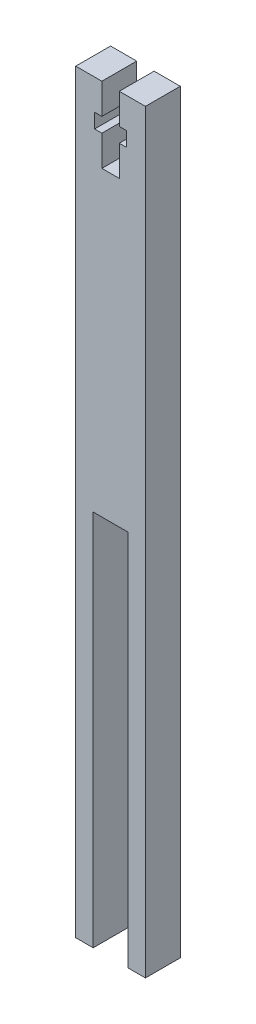
SolidWorks part; units mm, degrees
ref_plane "Спереди" through (0, 0, 0) normal (0, 0, 1) x (1, 0, 0)
ref_plane "Сверху" through (0, 0, 0) normal (0, 1, 0) x (1, 0, 0)
ref_plane "Справа" through (0, 0, 0) normal (1, 0, 0) x (0, 0, -1)
other "Configuration Table"
sketch "Эскиз1" plane through (0, 0, 0) normal (0, 0, 1) x (1, 0, 0)
  line L0 (0, 0) -> (0, 130) construction
  line L1 (0, 65) -> (-21.3565, 65) construction
  line L2 (-1.5, 130) -> (-1.5, 124.75)
  line L3 (-1.5, 124.75) -> (-2.75, 124.75)
  line L4 (-2.75, 124.75) -> (-2.75, 122.25)
  line L5 (-2.75, 122.25) -> (-1.5, 122.25)
  line L6 (-1.5, 122.25) -> (-1.5, 117)
  line L7 (-1.5, 117) -> (1.5, 117)
  line L8 (1.5, 122.25) -> (1.5, 117)
  line L9 (2.75, 122.25) -> (1.5, 122.25)
  line L10 (2.75, 124.75) -> (2.75, 122.25)
  line L11 (1.5, 124.75) -> (2.75, 124.75)
  line L12 (1.5, 130) -> (1.5, 124.75)
  line L25 (-1.5, 130) -> (-6, 130)
  line L26 (-6, 130) -> (-6, 0)
  line L28 (6, 130) -> (6, 0)
  line L29 (1.5, 130) -> (6, 130)
  line L30 (-6, 0) -> (-3, 0)
  line L31 (-3, 0) -> (-3, 65)
  line L32 (-3, 65) -> (3, 65)
  line L33 (3, 0) -> (3, 65)
  line L34 (6, 0) -> (3, 0)
  point P13 (0, 117)
  point P18 (2.75, 123.5)
  point P23 (0, 65)
  dimension "D1" = 2.5
  dimension "D2" = 3
  dimension "D3" = 5.5
  dimension "D4" = 13
  dimension "D5" = 6
  dimension "D6" = 12
  dimension "D7" = 130
extrude "Бобышка-Вытянуть1" add sketch "Эскиз1" along normal blind 6
